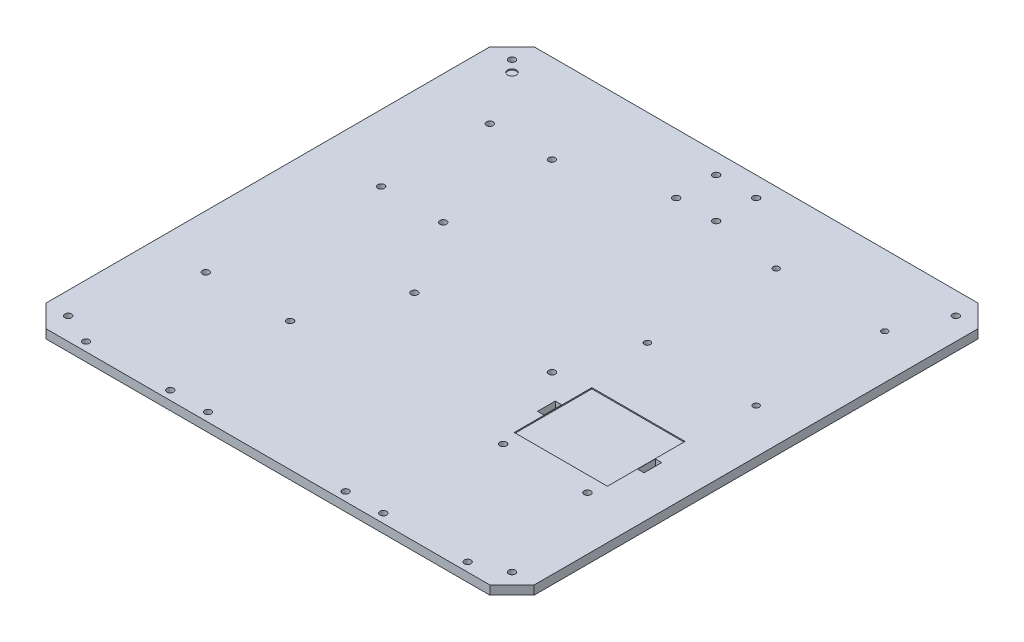
SolidWorks part; units mm, degrees
ref_plane "Front" through (0, 0, 0) normal (0, 0, 1) x (1, 0, 0)
ref_plane "Top" through (0, 0, 0) normal (0, 1, 0) x (1, 0, 0)
ref_plane "Right" through (0, 0, 0) normal (1, 0, 0) x (0, 0, -1)
sketch "Sketch1" plane through (0, 0, 0) normal (0, 1, 0) x (1, 0, 0)
  line L1 (0, 0) -> (220, 0)
  line L2 (0, 0) -> (0, 220)
  line L3 (0, 220) -> (220, 220)
  line L4 (220, 0) -> (220, 220)
  dimension "D1" = 220
  dimension "D2" = 220
extrude "Boss-Extrude1" add sketch "Sketch1" along normal blind 4
sketch "Sketch2" plane through (0, 4, 0) normal (0, 1, 0) x (1, 0, 0)
  line L0 (220, 0) -> (220, 220) construction
  line L1 (0, 0) -> (220, 0) construction
  circle A0 centre (196, 4) radius 1.5
  circle A1 centre (158, 4) radius 1.5
  circle A2 centre (196, 58) radius 1.5
  circle A3 centre (158, 58) radius 1.5
  dimension "D5" = 3
  dimension "D6" = 3
  dimension "D7" = 24
  dimension "D11" = 3
  dimension "D12" = 3
  dimension "D1" = 24
  dimension "D2" = 4
  dimension "D3" = 4
  dimension "D4" = 38
  dimension "D8" = 38
  dimension "D9" = 54
  dimension "D10" = 54
extrude "Cut-Extrude1" cut sketch "Sketch2" against normal blind 8
sketch "Sketch3" plane through (0, 4, 0) normal (0, 1, 0) x (1, 0, 0)
  line L0 (0, 220) -> (0, 0) construction
  line L1 (0, 0) -> (220, 0) construction
  circle A0 centre (62, 4) radius 1.5
  circle A1 centre (24, 4) radius 1.5
  circle A2 centre (62, 58) radius 1.5
  circle A3 centre (24, 58) radius 1.5
  dimension "D9" = 3
  dimension "D10" = 3
  dimension "D11" = 3
  dimension "D12" = 3
  dimension "D1" = 24
  dimension "D2" = 24
  dimension "D3" = 54
  dimension "D4" = 4
  dimension "D5" = 4
  dimension "D6" = 38
  dimension "D7" = 38
  dimension "D8" = 54
extrude "Cut-Extrude2" cut sketch "Sketch3" against normal blind 8
chamfer "Chamfer1" distance 10 angle 45 4 edges at (0, 2, -220) (220, 2, -220) (220, 2, 0) (0, 2, 0)
sketch "Sketch4" plane through (0, 4, 0) normal (0, 1, 0) x (1, 0, 0)
  line L0 (210, 220) -> (10, 220) construction
  line L1 (220, 10) -> (220, 210) construction
  circle A0 centre (151, 130) radius 1.375
  circle A1 centre (200, 130) radius 1.375
  circle A2 centre (151, 188) radius 1.375
  circle A3 centre (200, 188) radius 1.375
  dimension "D9" = 2.75
  dimension "D10" = 2.75
  dimension "D11" = 2.75
  dimension "D12" = 2.75
  dimension "D1" = 90
  dimension "D2" = 90
  dimension "D3" = 20
  dimension "D4" = 49
  dimension "D5" = 20
  dimension "D6" = 49
  dimension "D7" = 58
  dimension "D8" = 58
extrude "Cut-Extrude3" cut sketch "Sketch4" against normal blind 4
sketch "Sketch5" plane through (0, 4, 0) normal (0, 1, 0) x (1, 0, 0)
  line L0 (210, 220) -> (10, 220) construction
  line L1 (0, 210) -> (0, 10) construction
  circle A0 centre (15, 205) radius 2
  dimension "D3" = 4
  dimension "D1" = 15
  dimension "D2" = 15
extrude "Cut-Extrude4" cut sketch "Sketch5" against normal blind 0.5
sketch "Sketch6" plane through (0, 4, 0) normal (0, 1, 0) x (1, 0, 0)
  line L5 (156, 100) -> (198, 100)
  line L6 (156, 100) -> (156, 65)
  line L7 (156, 65) -> (198, 65)
  line L8 (198, 100) -> (198, 65)
  line L9 (220, 10) -> (220, 210) construction
  line L10 (10, 0) -> (210, 0) construction
  dimension "D2" = 22
  dimension "D3" = 42
  dimension "D4" = 35
  dimension "D8" = 65
extrude "Cut-Extrude5" cut sketch "Sketch6" against normal blind 0.5
sketch "Sketch7" plane through (0, 4, 0) normal (0, 1, 0) x (1, 0, 0)
  line L0 (198.1, 78.5) -> (198.1, 86.5)
  line L5 (201, 78.5) -> (198.1, 78.5)
  line L14 (153, 86.5) -> (153, 78.5)
  line L19 (201, 86.5) -> (201, 78.5)
  line L20 (198.1, 86.5) -> (201, 86.5)
  line L21 (198, 65) -> (198, 100) construction
  line L24 (153, 78.5) -> (155.9, 78.5)
  line L25 (155.9, 78.5) -> (155.9, 86.5)
  line L26 (155.9, 86.5) -> (153, 86.5)
  line L27 (156, 100) -> (156, 65) construction
  line L28 (156, 65) -> (198, 65) construction
  dimension "D1" = 2.9
  dimension "D2" = 2.9
  dimension "D3" = 8
  dimension "D4" = 8
  dimension "D5" = 0.1
  dimension "D6" = 0.1
  dimension "D7" = 13.5
  dimension "D8" = 13.5
extrude "Cut-Extrude6" cut sketch "Sketch7" against normal through all
sketch "Sketch9" plane through (0, 4, 0) normal (0, 1, 0) x (1, 0, 0)
  line L0 (0, 210) -> (0, 10) construction
  line L2 (210, 220) -> (10, 220) construction
  circle A0 centre (30, 180) radius 1.5
  circle A1 centre (58, 180) radius 1.5
  circle A2 centre (58, 131) radius 1.5
  circle A3 centre (30, 131) radius 1.5
  dimension "D8" = 3
  dimension "D9" = 3
  dimension "D10" = 3
  dimension "D11" = 3
  dimension "D1" = 28
  dimension "D2" = 28
  dimension "D3" = 30
  dimension "D4" = 30
  dimension "D5" = 49
  dimension "D6" = 49
  dimension "D7" = 40
extrude "Cut-Extrude7" cut sketch "Sketch9" against normal blind 8
sketch "Sketch10" plane through (0, 4, 0) normal (0, 1, 0) x (1, 0, 0)
  line L0 (0, 210) -> (0, 10) construction
  line L1 (210, 220) -> (10, 220) construction
  line L2 (10, 0) -> (210, 0) construction
  line L3 (220, 10) -> (220, 210) construction
  circle A0 centre (10, 210) radius 1.5
  circle A1 centre (10, 10) radius 1.5
  circle A2 centre (210, 10) radius 1.5
  circle A3 centre (210, 210) radius 1.5
  dimension "D9" = 3
  dimension "D10" = 3
  dimension "D11" = 3
  dimension "D12" = 3
  dimension "D1" = 10
  dimension "D2" = 10
  dimension "D3" = 10
  dimension "D4" = 10
  dimension "D5" = 10
  dimension "D6" = 10
  dimension "D7" = 10
  dimension "D8" = 10
extrude "Cut-Extrude8" cut sketch "Sketch10" against normal through all
sketch "Sketch11" plane through (0, 4, 0) normal (0, 1, 0) x (1, 0, 0)
  line L0 (110, 0) -> (110, 220) construction
  line L1 (10, 0) -> (210, 0) construction
  line L2 (210, 220) -> (10, 220) construction
  line L4 (119, 193.0012) -> (101, 193.0012)
  line L5 (119, 193.0012) -> (119, 211.0012)
  line L6 (119, 211.0012) -> (101, 211.0012)
  line L7 (101, 193.0012) -> (101, 211.0012)
  circle A0 centre (119, 193.0012) radius 1.5
  circle A1 centre (119, 211.0012) radius 1.5
  circle A2 centre (101, 211.0012) radius 1.5
  circle A3 centre (101, 193.0012) radius 1.5
  dimension "D5" = 3
  dimension "D6" = 3
  dimension "D7" = 3
  dimension "D8" = 3
  dimension "D1" = 18
  dimension "D2" = 18
  dimension "D3" = 9
  dimension "D4" = 8.9988
extrude "Cut-Extrude9" cut sketch "Sketch11" against normal blind 46 contours L4 A0 L5 | L4 A3 L7 | L7 A3 L4 | L5 A0 L4 | L7 A2 L6 | L6 A2 L7 | L6 A1 L5 | L5 A1 L6
sketch "Sketch12" plane through (0, 4, 0) normal (0, 1, 0) x (1, 0, 0)
  line L0 (10, 0) -> (210, 0) construction
  line L1 (220, 10) -> (220, 210) construction
  circle A0 centre (141, 4) radius 1.5
  circle A1 centre (79, 4) radius 1.5
  circle A2 centre (141, 97) radius 1.5
  circle A3 centre (79, 97) radius 1.5
  dimension "D6" = 3
  dimension "D7" = 3
  dimension "D8" = 3
  dimension "D9" = 3
  dimension "D1" = 93
  dimension "D2" = 62
  dimension "D3" = 93
  dimension "D4" = 62
  dimension "D5" = 4
  dimension "D10" = 79
extrude "Cut-Extrude11" cut sketch "Sketch12" against normal through all
